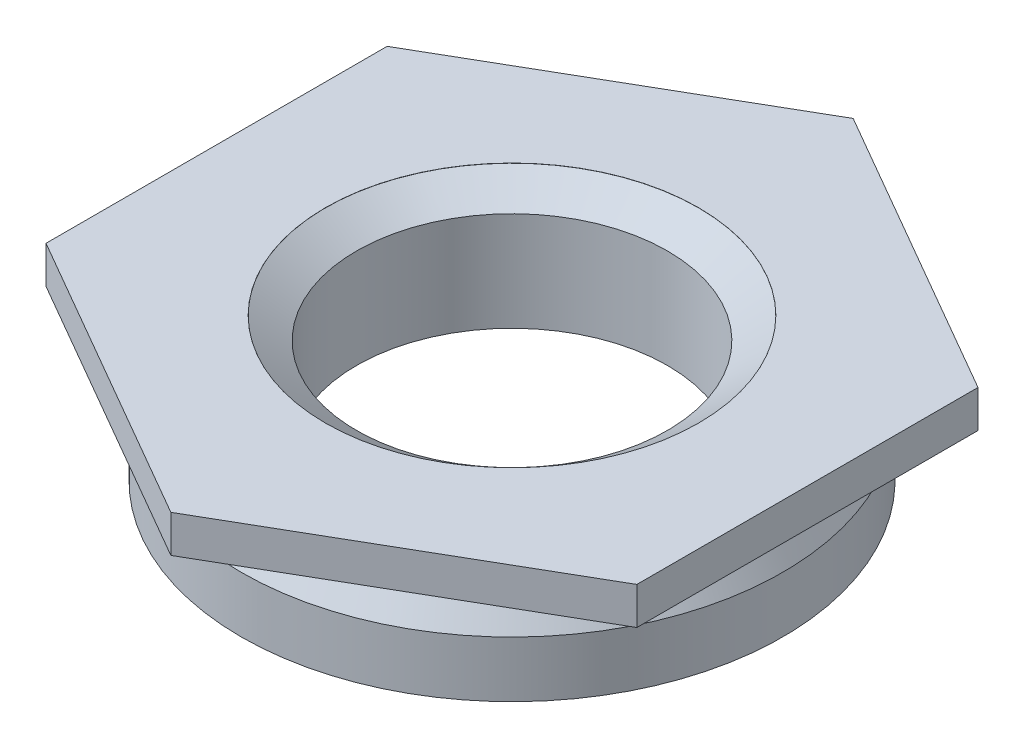
SolidWorks part; units mm, degrees
revolve "Body" add sketch "BodySke"
sketch "BodySke" plane through (0, 0, 0) normal (0, 0, 1) x (1, 0, 0)
  line L0 (4.0663, 0) -> (5.5095, 0)
  line L1 (5.5095, 0) -> (5.5095, 0.6)
  line L2 (5.5095, 0.6) -> (2.5, 0.6)
  line L3 (2.5, 0.6) -> (2.5, -1.7)
  line L4 (2.5, -1.7) -> (4.355, -1.7)
  line L5 (4.355, -1.7) -> (4.355, -0.8)
  line L6 (4.355, -0.8) -> (4.0663, -0.3)
  line L7 (1.016, 1) -> (3.6522, 1) construction
  line L9 (0, 0) -> (0, 15.24) construction
  line L10 (4.0663, -0.3) -> (4.0663, 0)
  dimension "E_dia" = 11.019
  dimension "C_dia" = 8.71
  dimension "A_ht" = 1.7
  dimension "Thread_min" = 5
  dimension "C_len" = 0.9
  dimension "Clinching_ht" = 0.3
  dimension "D1" = 60
  dimension "Advance" = 1
  dimension "Thickness" = 2.3
cosmetic thread "ThreadCosmetic" [suppressed]
revolve "EndChamfer" cut sketch "EndChamferSke" angle 360 about L0
sketch "EndChamferSke" plane through (0, 0, 0) normal (0, 0, 1) x (1, 0, 0)
  line L0 (0, -2.54) -> (0, 7.62) construction
  line L1 (0, 0) -> (0, 15.24) construction
  line L2 (3, -1.954) -> (3, -1.6975)
  line L3 (3, -1.6975) -> (2.5, -1.3475)
  line L4 (2.5, -1.3475) -> (2.5, -1.954)
  line L5 (2.5, -1.954) -> (3, -1.954)
  line L6 (3, 0.5975) -> (2.5, 0.2475)
  line L7 (3, 0.5975) -> (3, 0.854)
  line L8 (2.5, 0.2475) -> (2.5, 0.854)
  line L9 (3, 0.854) -> (2.5, 0.854)
  line L11 (-4.355, -1.7) -> (4.355, -1.7) construction
  line L12 (5.5095, 0.6) -> (-5.5095, 0.6) construction
  dimension "Thread_min" = 5
  dimension "Thread_nominal" = 6
  dimension "D1" = 0.254
  dimension "D2" = 34.99
  dimension "D3" = 0.254
ref_plane "Plane1" through (0, 0, 0) normal (0, 0, 1) x (1, 0, 0)
ref_plane "Plane2" through (0, 0, 0) normal (0, 1, 0) x (1, 0, 0)
ref_plane "Plane3" through (0, 0, 0) normal (1, 0, 0) x (0, 0, -1)
ref_plane "Plane4" through (0, -0.5486, 0) normal (0, 1, 0) x (-1, 0, 0)
sketch "ThdSchSke" plane through (0, 0, 0) normal (0, 0, 1) x (1, 0, 0)
  line L0 (0, -5.08) -> (0, 7.62) construction
  line L1 (0, 0) -> (0, 15.24) construction
  line L2 (0, -1.6975) -> (3, -1.6975) construction
  line L4 (3, -1.6975) -> (2.5, -1.3474)
  line L6 (3, -1.6975) -> (2.5, -2.0476)
  line L7 (2.5, -1.3474) -> (2.5, -2.0476)
  line L8 (3, -1.6975) -> (-3, -1.6975) construction
  dimension "Thread_min" = 5
  dimension "Thread_nominal" = 6
revolve "ThreadSchematic" [suppressed] cut sketch "ThdSchSke" angle 360 about L0
pattern_linear "ThdSchPat" [suppressed]
sketch "HexDieSke" plane through (0, 0.6, 0) normal (0, 1, 0) x (-1, 0, 0)
  line L0 (0, 5.4848) -> (4.75, 2.7424)
  line L1 (4.75, 2.7424) -> (4.75, -2.7424)
  line L2 (4.75, -2.7424) -> (0, -5.4848)
  line L3 (0, -5.4848) -> (-4.75, -2.7424)
  line L4 (-4.75, -2.7424) -> (-4.75, 2.7424)
  line L5 (-4.75, 2.7424) -> (0, 5.4848)
  circle A1 centre (0, 0) radius 4.75 construction
  circle A2 centre (0, 0) radius 5.4848 construction
  circle A3 centre (0, 0) radius 5.5105
  dimension "Width_across_flats" = 9.5
  dimension "OD" = 11.021
extrude "HexDie" cut sketch "HexDieSke" against normal blind 0.6
equation "' \"Thickness@BodySke\" = 2.3"
equation "' \"C_dia@BodySke\" = 8.71"
equation "' \"Width_across_flats@HexDieSke\" = 9.5"
equation "' \"Advance@BodySke\" = 1"
equation "' \"Thread_min@BodySke\" = 5"
equation "' \"Thread_nominal@ThreadCosmetic\" = 6"
equation "\"OD@HexDieSke\" =  \"Width_across_flats@HexDieSke\" * 1.16 + 0.001"
equation "\"E_dia@BodySke\" = \"Width_across_flats@HexDieSke\" * 1.16 - 0.001"
equation "\"A_ht@BodySke\" = \"Thickness@BodySke\" - 1.5 * 0.4"
equation "\"Depth@HexDie\" = \"Thickness@BodySke\" - \"A_ht@BodySke\""
equation "\"Clinching_ht@BodySke\" = 0.3"
equation "\"C_len@BodySke\" =  \"Thickness@BodySke\" - 1.4"
equation "\"Thread_nominal@EndChamferSke\" = \"Thread_nominal@ThreadCosmetic\""
equation "\"Thread_min@EndChamferSke\" = \"Thread_min@BodySke\""
equation "\"D2@EndChamferSke\" = \"Vee_angle@ThdSchSke\" / 2 - 0.01"
equation "\"Thread_nominal@ThdSchSke\" = \"Thread_nominal@ThreadCosmetic\""
equation "\"Thread_min@ThdSchSke\" = \"Thread_min@BodySke\""
equation "\"Num_threads@ThdSchPat\" = int(  ( \"Thickness@BodySke\" - \"Inset@EndChamferSke\" - \"Inset_far@EndChamferSke\" ) / \"Advance@BodySke\" + 0.999 )  + 1"
equation "\"Advance@ThdSchPat\" = (  \"Thickness@BodySke\" - \"Inset@EndChamferSke\" - \"Inset_far@EndChamferSke\"  ) /  (\"Num_threads@ThdSchPat\" - 1) 'relax it"
